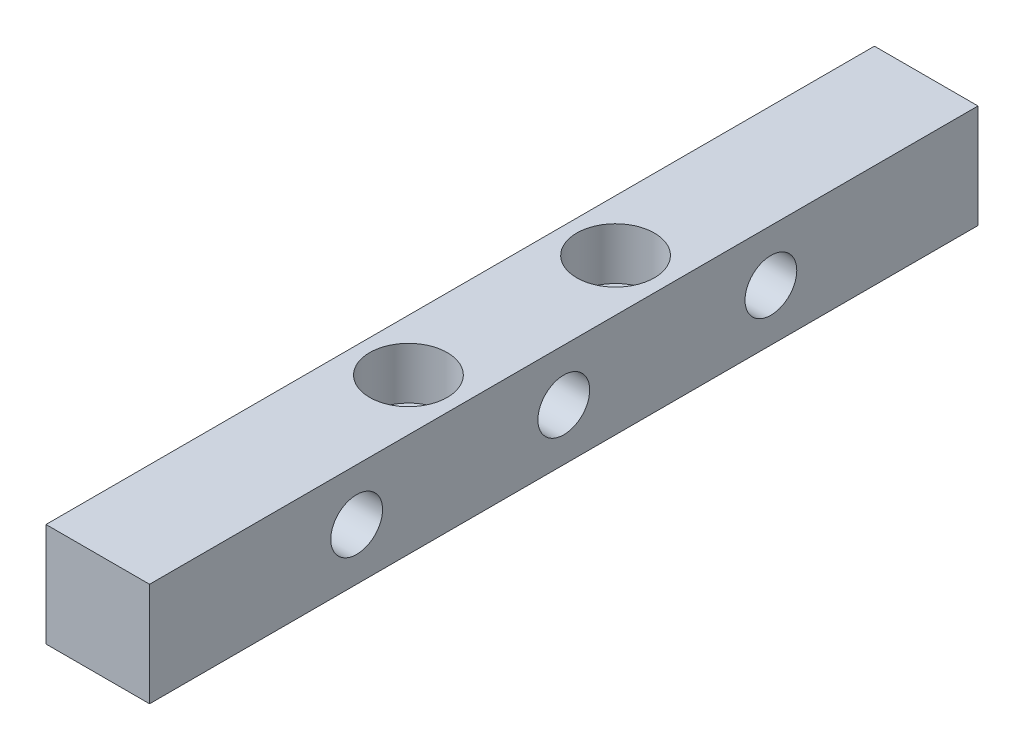
SolidWorks part; units mm, degrees
material "6061 Alloy"
ref_plane "Front" through (0, 0, 0) normal (0, 0, 1) x (1, 0, 0)
ref_plane "Top" through (0, 0, 0) normal (0, 1, 0) x (1, 0, 0)
ref_plane "Right" through (0, 0, 0) normal (1, 0, 0) x (0, 0, -1)
sketch "Sketch2" plane through (0, 0, 0) normal (0, 0, 1) x (1, 0, 0)
  line L0 (-6.35, -6.35) -> (6.35, -6.35)
  line L7 (-6.35, 6.35) -> (6.35, 6.35)
  line L8 (0, -6.35) -> (0, 6.35) construction
  line L9 (-6.35, -6.35) -> (-6.35, 6.35)
  line L11 (6.35, -6.35) -> (6.35, 6.35)
  dimension "D1" = 12.7
  dimension "D2" = 12.7
extrude "Boss-Extrude1" add sketch "Sketch2" along normal mid plane 101.6
hole_wizard "1/4\"-20 threaded C-Bore" positions "Sketch7" profile "Sketch6" counterbore size "#10" standard "ANSI Inch" end condition through all
sketch "Sketch7" plane through (0, 6.35, 0) normal (0, 1, 0) x (1, 0, 0)
  line L0 (0, 12.7) -> (0, -12.7) construction
  point P18 (0, 12.7)
  point P20 (0, -12.7)
  dimension "D1" = 25.4
sketch "Sketch6" plane through (0, 6.35, -12.7) normal (1, 0, 0) x (0, 0, 1)
  line L0 (0, 0) -> (0, 12.7)
  line L1 (0, 12.7) -> (3.175, 12.7)
  line L3 (3.175, 12.7) -> (3.175, 6.35)
  line L4 (3.175, 6.35) -> (4.7625, 6.35)
  line L5 (4.7625, 6.35) -> (4.7625, 0)
  line L7 (4.7625, 0) -> (0, 0)
  line L11 (0, -6.35) -> (0, 107.95) construction
  dimension "Thru Hole Dia." = 6.35
  dimension "Thru Hole Depth" = 12.7
  dimension "C'Bore Dia." = 9.525
  dimension "C'Bore Depth" = 6.35
hole_wizard "1/4\"-20 threaded hole" positions "Sketch9" profile "Sketch8" hole size "#97" standard "ANSI Inch" end condition through all
sketch "Sketch9" plane through (6.35, 0, 0) normal (1, 0, 0) x (0, 0, -1)
  point P0 (-25.4, 0)
  point P2 (0, 0)
  point P5 (25.4, 0)
  dimension "D1" = 25.4
  dimension "D2" = 25.4
sketch "Sketch8" plane through (6.35, 0, 25.4) normal (0, 1, 0) x (0, 0, -1)
  line L0 (0, 0) -> (0, 12.7)
  line L1 (0, 12.7) -> (3.175, 12.7)
  line L2 (3.175, 12.7) -> (3.175, 0)
  line L5 (3.175, 0) -> (0, 0)
  line L11 (0, -6.35) -> (0, 107.95) construction
  dimension "Thru Hole Dia." = 6.35
  dimension "Thru Hole Depth" = 12.7
